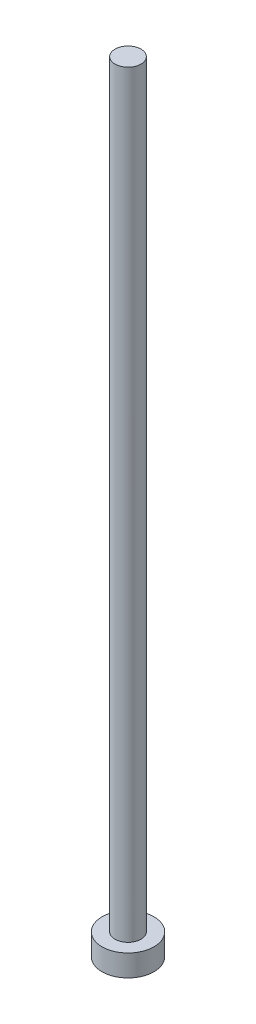
SolidWorks part; units mm, degrees
ref_plane "Front Plane" through (0, 0, 0) normal (0, 0, 1) x (1, 0, 0)
ref_plane "Top Plane" through (0, 0, 0) normal (0, 1, 0) x (1, 0, 0)
ref_plane "Right Plane" through (0, 0, 0) normal (1, 0, 0) x (0, 0, -1)
sketch "Sketch1" plane through (0, 0, 0) normal (0, 1, 0) x (1, 0, 0)
  circle A0 centre (0, 0) radius 3
  dimension "D1" = 6
extrude "Boss-Extrude1" add sketch "Sketch1" along normal blind 175
sketch "Sketch2" plane through (0, 0, 0) normal (0, -1, 0) x (1, 0, 0)
  circle A0 centre (0, 0) radius 6
  dimension "D1" = 12
extrude "Boss-Extrude2" add sketch "Sketch2" along normal blind 5
